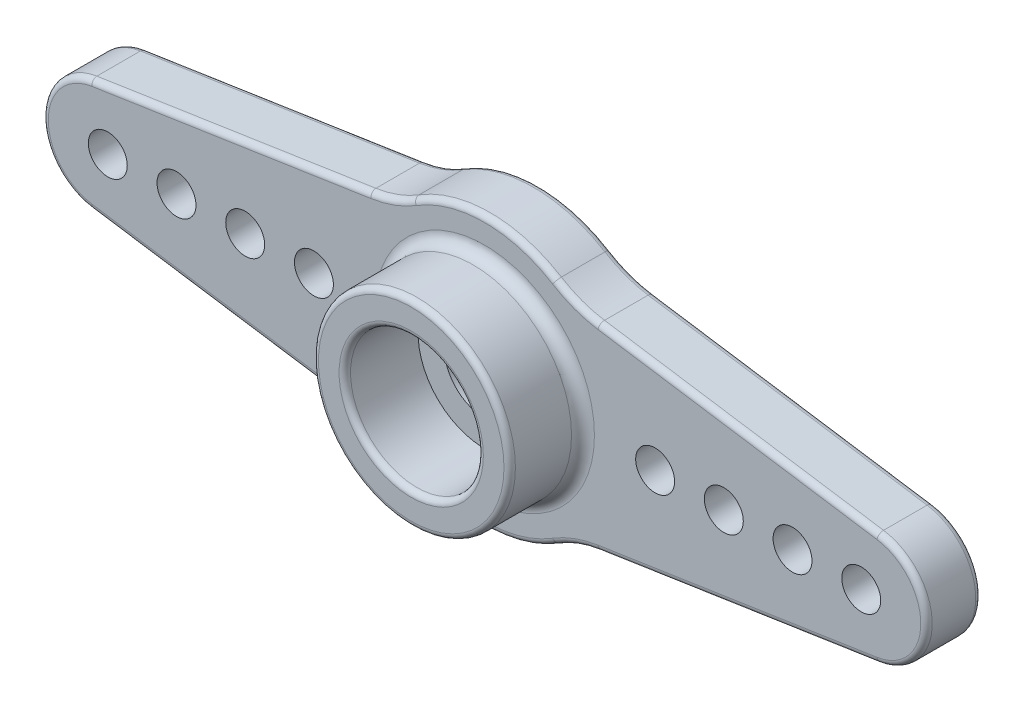
SolidWorks part; units mm, degrees
ref_plane "Front Plane" through (0, 0, 0) normal (0, 0, 1) x (1, 0, 0)
ref_plane "Top Plane" through (0, 0, 0) normal (0, 1, 0) x (1, 0, 0)
ref_plane "Right Plane" through (0, 0, 0) normal (1, 0, 0) x (0, 0, -1)
sketch "Sketch1" plane through (0, 0, 0) normal (0, 0, 1) x (1, 0, 0)
  line L0 (-4.9917, 4.3215) -> (-17.1753, 2.4717)
  line L1 (-17.1753, -2.4717) -> (-4.9917, -4.3215)
  line L2 (0, 0) -> (0, 9.7744) construction
  line L3 (0, 0) -> (-16.8, 0) construction
  line L4 (17.1753, -2.4717) -> (4.9917, -4.3215)
  line L5 (4.9917, 4.3215) -> (17.1753, 2.4717)
  arc A0 (-3.1082, -5.0149) -> (3.1082, -5.0149) centre (0, 0) ccw
  circle A1 centre (0, 0) radius 1.75
  arc A2 (-17.1753, 2.4717) -> (-17.1753, -2.4717) centre (-16.8, 0) ccw
  arc A3 (17.1753, 2.4717) -> (17.1753, -2.4717) centre (16.8, 0) cw
  arc A4 (3.1082, 5.0149) -> (-3.1082, 5.0149) centre (0, 0) ccw
  arc A5 (-4.9917, -4.3215) -> (-3.1082, -5.0149) centre (-5.7422, -9.2648) cw
  arc A6 (3.1082, -5.0149) -> (4.9917, -4.3215) centre (5.7422, -9.2648) cw
  arc A7 (4.9917, 4.3215) -> (3.1082, 5.0149) centre (5.7422, 9.2648) cw
  arc A8 (-3.1082, 5.0149) -> (-4.9917, 4.3215) centre (-5.7422, 9.2648) cw
  point P17 (-3.8158, -4.5)
  point P20 (3.8158, -4.5)
  point P23 (3.8158, 4.5)
  point P26 (-3.8158, 4.5)
  dimension "D1" = 11.8
  dimension "D2" = 3.5
  dimension "D3" = 2.5
  dimension "D6" = 5
  dimension "D4" = 33.6
  dimension "D5" = 9
extrude "Boss-Extrude1" add sketch "Sketch1" along normal blind 2.4
sketch "Sketch2" plane through (0, 0, 2.4) normal (0, 0, 1) x (1, 0, 0)
  circle A0 centre (0, 0) radius 4.3
  circle A1 centre (0, 0) radius 2.9
  dimension "D1" = 8.6
  dimension "D2" = 5.8
extrude "Boss-Extrude2" add sketch "Sketch2" along normal blind 3.2
sketch "Sketch4" plane through (0, 0, 0) normal (0, 0, -1) x (-1, 0, 0)
  circle A0 centre (0, 0) radius 3.3
  circle A1 centre (0, 0) radius 3.6
  dimension "D1" = 7.2
  dimension "D2" = 6.6
extrude "Boss-Extrude3" add sketch "Sketch4" along normal blind 0.2
sketch "Sketch5" plane through (0, 0, 0) normal (0, 0, -1) x (-1, 0, 0)
  circle A0 centre (0, 0) radius 3.3 construction
  circle A1 centre (0, 0) radius 3.3
  circle A2 centre (0, 0) radius 4
  circle A3 centre (0, 0) radius 3.6 construction
  circle A4 centre (0, 0) radius 3.6
  dimension "D1" = 8
extrude "Cut-Extrude2" cut sketch "Sketch5" against normal blind 0.4
sketch "Sketch6" plane through (0, 0, 0) normal (0, 0, -1) x (-1, 0, 0)
  line L0 (0, 0) -> (0, 1.0197) construction
  circle A1 centre (7.45, 0) radius 0.85
  dimension "D1" = 1.7
  dimension "D2" = 7.45
extrude "Cut-Extrude3" cut sketch "Sketch6" against normal through all
pattern_linear "LPattern1" count 4 spacing 3 along (-1, 0, 0) of "Cut-Extrude3"
mirror "Mirror1" about plane through (0, 0, 0) normal (1, 0, 0) of "LPattern1", "Cut-Extrude3"
fillet "Fillet1" radius 0.25 26 edges at (4.3, 0, 5.6) (0, -5.9, 2.4) (0, -5.9, 0) (2.9, 0, 5.6) (-4.0148, -4.5727, 2.4) (-11.0835, -3.3966, 2.4) (-19.3, 0, 2.4) (-11.0835, 3.3966, 2.4) (-4.0148, 4.5727, 2.4) (0, 5.9, 2.4) (4.0148, 4.5727, 2.4) (11.0835, 3.3966, 2.4) (19.3, 0, 2.4) (11.0835, -3.3966, 2.4) (4.0148, -4.5727, 2.4) (-4.0148, -4.5727, 0) (-11.0835, -3.3966, 0) (-19.3, 0, 0) (-11.0835, 3.3966, 0) (-4.0148, 4.5727, 0) (0, 5.9, 0) (4.0148, 4.5727, 0) (11.0835, 3.3966, 0) (19.3, 0, 0) (11.0835, -3.3966, 0) (4.0148, -4.5727, 0)
fillet "Fillet2" radius 0.5 1 edges at (4.3, 0, 2.4)
